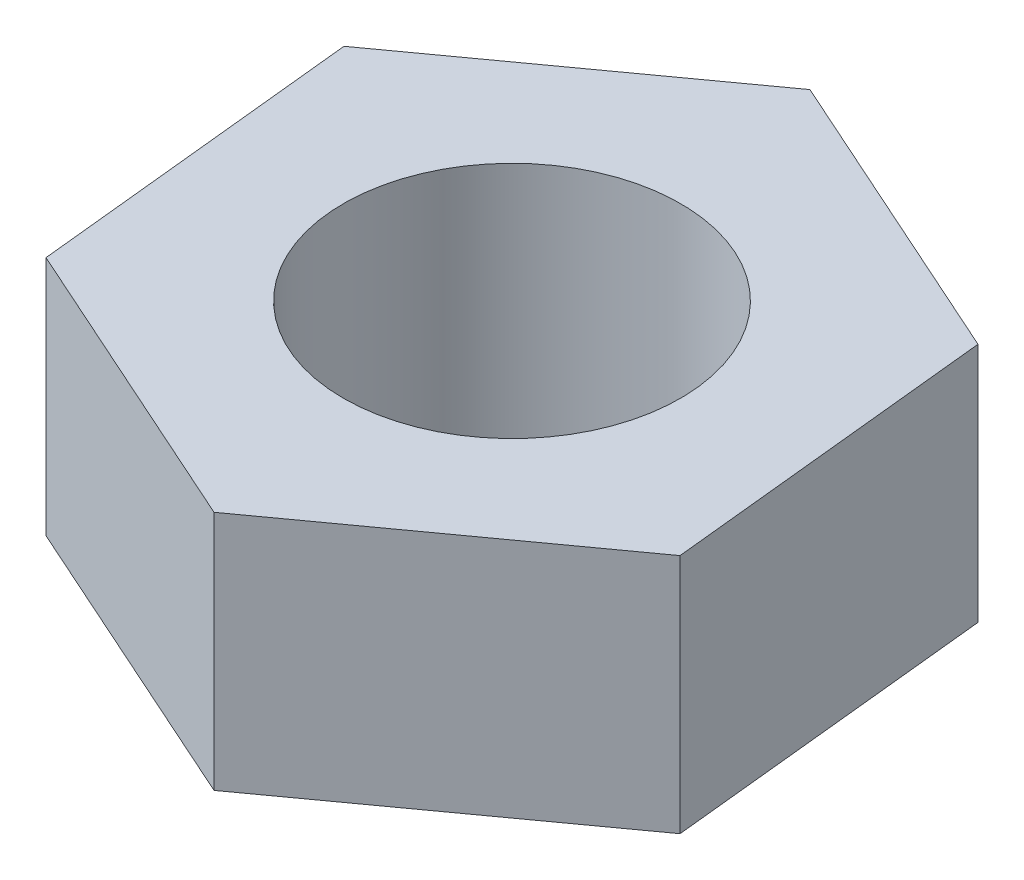
SolidWorks part; units mm, degrees
ref_plane "Front Plane" through (0, 0, 0) normal (0, 0, 1) x (1, 0, 0)
ref_plane "Top Plane" through (0, 0, 0) normal (0, 1, 0) x (1, 0, 0)
ref_plane "Right Plane" through (0, 0, 0) normal (1, 0, 0) x (0, 0, -1)
sketch "Sketch1" plane through (0, 0, 0) normal (0, 1, 0) x (1, 0, 0)
  line L1 (11.2305, 8.1164) -> (-1.4137, 13.7841)
  line L2 (-1.4137, 13.7841) -> (-12.6442, 5.6677)
  line L3 (-12.6442, 5.6677) -> (-11.2305, -8.1164)
  line L4 (-11.2305, -8.1164) -> (1.4137, -13.7841)
  line L5 (1.4137, -13.7841) -> (12.6442, -5.6677)
  line L6 (12.6442, -5.6677) -> (11.2305, 8.1164)
  circle A0 centre (0, 0) radius 12 construction
  circle A1 centre (0, 0) radius 7
  dimension "D1" = 24
  dimension "D2" = 14
extrude "Boss-Extrude1" add sketch "Sketch1" along normal blind 10
